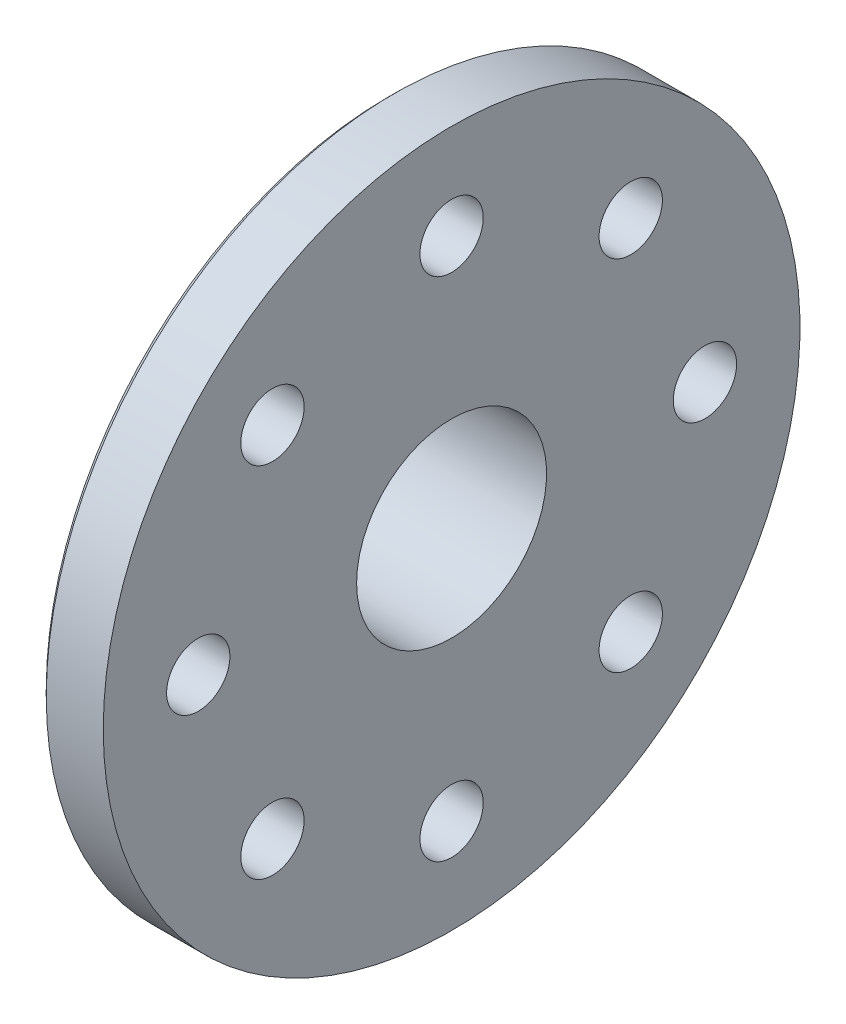
SolidWorks part; units mm, degrees
ref_plane "Ön Düzlem" through (0, 0, 0) normal (0, 0, 1) x (1, 0, 0)
ref_plane "Üst Düzlem" through (0, 0, 0) normal (0, 1, 0) x (1, 0, 0)
ref_plane "Sağ Düzlem" through (0, 0, 0) normal (1, 0, 0) x (0, 0, -1)
sketch "Sketch1" plane through (0, 0, 0) normal (0, 0, 1) x (1, 0, 0)
  line L0 (1, 11) -> (-1, 11)
  line L1 (-1, 11) -> (-1, 3.75)
  line L2 (-1, 3.75) -> (-4, 3.75)
  line L3 (-4, 3.75) -> (-4, 1.5)
  line L4 (-3.5, 3) -> (1, 3)
  line L5 (1, 3) -> (1, 11)
  line L6 (0, 11) -> (0, 0) construction
  line L7 (-3.5, 3) -> (-3.5, 1.5)
  line L8 (-3.5, 1.5) -> (-4, 1.5)
  line L9 (0, 0) -> (1.649, 0) construction
  dimension "D1" = 3
  dimension "D2" = 2
  dimension "D3" = 3
  dimension "D4" = 11
  dimension "D5" = 3.75
  dimension "D6" = 1.5
  dimension "D7" = 0.5
revolve "Revolve1" add sketch "Sketch1" angle 360 about L9
sketch "Sketch2" plane through (-1, 0, 0) normal (-1, 0, 0) x (0, 0, 1)
  circle A0 centre (0, 8) radius 1
  dimension "D1" = 2
  dimension "D2" = 8
extrude "Cut-Extrude1" cut sketch "Sketch2" against normal through all
pattern_circular "CirPattern1" count 8 over 360 about axis through (0, 0, 0) along (1, 0, 0) of "Cut-Extrude1"
chamfer "Chamfer1" distance 0.2 angle 45 10 edges at (-1, 0, 11) (-1, 8, 1) (-1, 6.364, -4.9497) (-1, 1, -8) (-1, -4.9497, -6.364) (-1, -8, -1) (-1, -6.364, 4.9497) (-1, -1, 8) (-1, 4.9497, 6.364) (-4, 0, 3.75)
